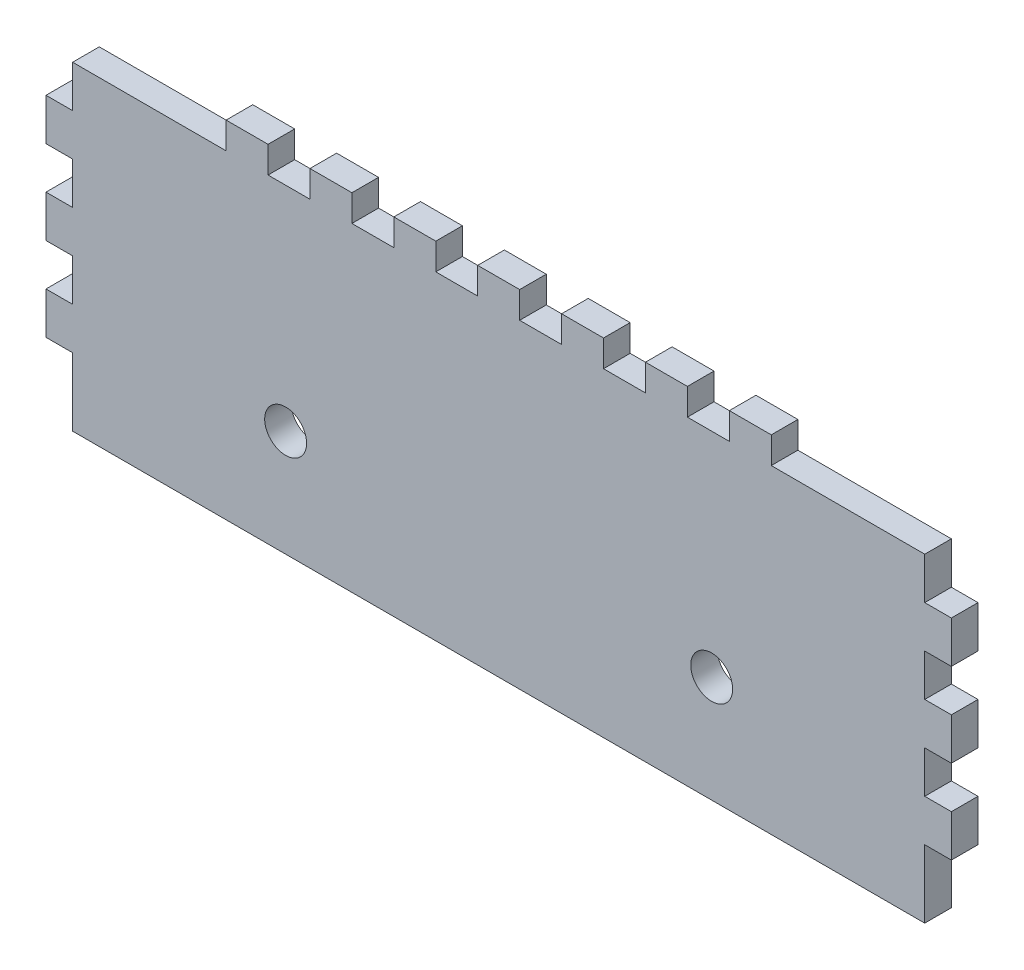
SolidWorks part; units mm, degrees
ref_plane "Front Plane" through (0, 0, 0) normal (0, 0, 1) x (1, 0, 0)
ref_plane "Top Plane" through (0, 0, 0) normal (0, 1, 0) x (1, 0, 0)
ref_plane "Right Plane" through (0, 0, 0) normal (1, 0, 0) x (0, 0, -1)
sketch "Sketch1" plane through (0, 0, 0) normal (0, 0, 1) x (1, 0, 0)
  line L0 (-101.6, -25.4) -> (0, -25.4) construction
  line L1 (-101.6, 0) -> (-83.3, 0)
  line L2 (0, 0) -> (0, -5)
  line L3 (0, -38.1) -> (-101.6, -38.1)
  line L4 (-101.6, 0) -> (-101.6, -5)
  line L7 (-28.3, 0) -> (-23.3, 0)
  line L8 (-23.3, 0) -> (-23.3, 3.175)
  line L9 (-23.3, 3.175) -> (-18.3, 3.175)
  line L16 (-83.3, 0) -> (-83.3, 3.175)
  line L17 (-83.3, 3.175) -> (-78.3, 3.175)
  line L18 (-78.3, 0) -> (-78.3, 3.175)
  line L19 (-78.3, 0) -> (-73.3, 0)
  line L20 (-73.3, 0) -> (-73.3, 3.175)
  line L21 (-73.3, 3.175) -> (-68.3, 3.175)
  line L22 (-68.3, 0) -> (-68.3, 3.175)
  line L23 (-68.3, 0) -> (-63.3, 0)
  line L24 (-63.3, 0) -> (-63.3, 3.175)
  line L25 (-63.3, 3.175) -> (-58.3, 3.175)
  line L26 (-58.3, 0) -> (-58.3, 3.175)
  line L27 (-58.3, 0) -> (-53.3, 0)
  line L28 (-53.3, 0) -> (-53.3, 3.175)
  line L29 (-53.3, 3.175) -> (-48.3, 3.175)
  line L30 (-48.3, 0) -> (-48.3, 3.175)
  line L31 (-48.3, 0) -> (-43.3, 0)
  line L32 (-43.3, 0) -> (-43.3, 3.175)
  line L33 (-43.3, 3.175) -> (-38.3, 3.175)
  line L34 (-38.3, 0) -> (-38.3, 3.175)
  line L35 (-38.3, 0) -> (-33.3, 0)
  line L36 (-33.3, 0) -> (-33.3, 3.175)
  line L37 (-33.3, 3.175) -> (-28.3, 3.175)
  line L38 (-28.3, 0) -> (-28.3, 3.175)
  line L39 (-18.3, 3.175) -> (-18.3, 0)
  line L40 (-18.3, 0) -> (0, 0)
  line L44 (-101.6, -10) -> (-101.6, -15)
  line L45 (-101.6, -5) -> (-104.775, -5)
  line L47 (-101.6, -15) -> (-104.775, -15)
  line L48 (-101.6, -10) -> (-104.775, -10)
  line L49 (-104.775, -5) -> (-104.775, -10)
  line L50 (-104.775, -15) -> (-104.775, -20)
  line L51 (-101.6, -20) -> (-104.775, -20)
  line L52 (-101.6, -20) -> (-101.6, -25)
  line L53 (-101.6, -25) -> (-104.775, -25)
  line L54 (-104.775, -25) -> (-104.775, -30)
  line L55 (-101.6, -30) -> (-104.775, -30)
  line L56 (-101.6, -30) -> (-101.6, -38.1)
  line L59 (-50.8, 27.452) -> (-50.8, -103.652) construction
  line L60 (3.175, -25) -> (3.175, -30)
  line L61 (3.175, -15) -> (3.175, -20)
  line L62 (3.175, -5) -> (3.175, -10)
  line L63 (3.175, -5) -> (0, -5)
  line L64 (3.175, -10) -> (0, -10)
  line L65 (3.175, -15) -> (0, -15)
  line L66 (3.175, -20) -> (0, -20)
  line L67 (3.175, -25) -> (0, -25)
  line L68 (3.175, -30) -> (0, -30)
  line L69 (0, -20) -> (0, -25)
  line L70 (0, -30) -> (0, -38.1)
  line L71 (0, -10) -> (0, -15)
  circle A0 centre (-76.2, -25.4) radius 2.5
  circle A1 centre (-25.4, -25.4) radius 2.5
  point P72 (-50.8, -38.1)
  dimension "D3" = 25.4
  dimension "D5" = 12.7
  dimension "D6" = 3.175
  dimension "D1" = 5
  dimension "D2" = 50.8
  dimension "D4" = 25.4
  dimension "D7" = 38.1
  dimension "D9" = 5
  dimension "D10" = 5
  dimension "D12" = 101.6
  dimension "D8" = 3.175
  dimension "D17" = 5
  dimension "D18" = 5
  dimension "D11" = 3
extrude "Boss-Extrude1" add sketch "Sketch1" along normal blind 3.175
sketch "Sketch2" plane through (0, 0, 3.175) normal (0, 0, 1) x (1, 0, 0)
